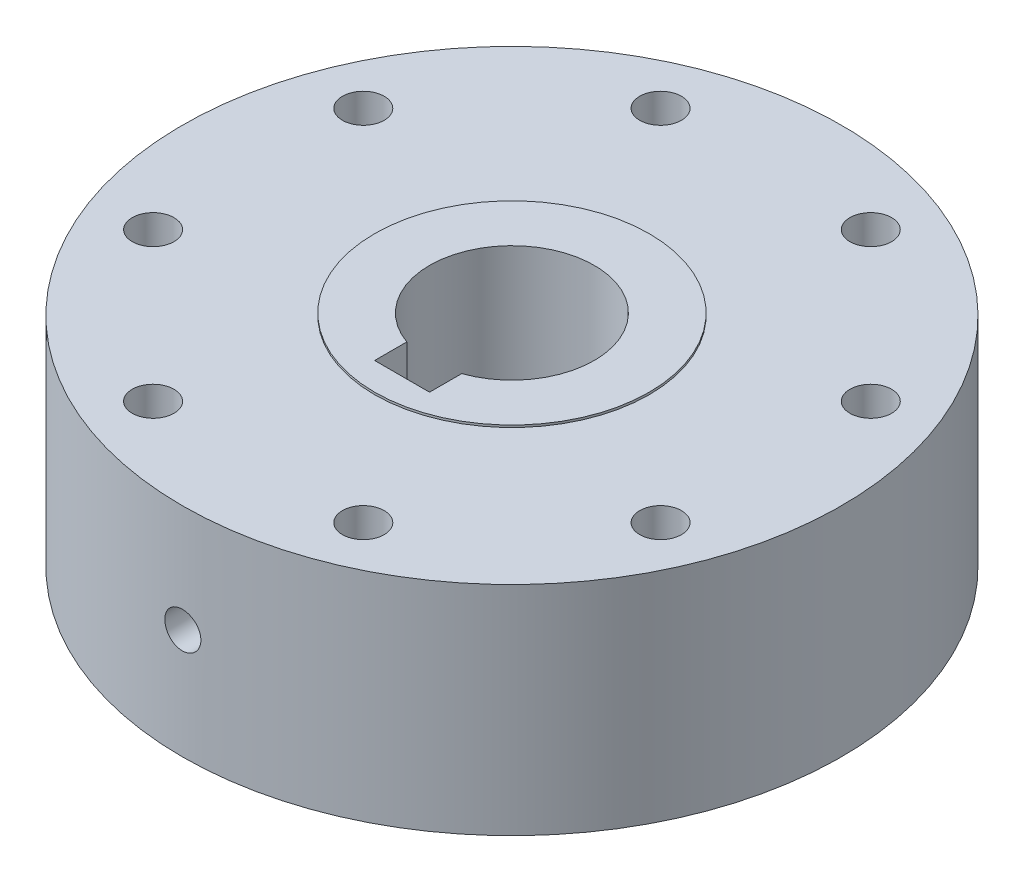
SolidWorks part; units mm, degrees
ref_plane "Front Plane" through (0, 0, 0) normal (0, 0, 1) x (1, 0, 0)
ref_plane "Top Plane" through (0, 0, 0) normal (0, 1, 0) x (1, 0, 0)
ref_plane "Right Plane" through (0, 0, 0) normal (1, 0, 0) x (0, 0, -1)
sketch "Sketch1" plane through (0, 0, 0) normal (0, 1, 0) x (1, 0, 0)
  circle A0 centre (0, 0) radius 38.1
  circle A1 centre (0, 0) radius 9.525
  dimension "D1" = 76.2
  dimension "D2" = 19.05
extrude "Boss-Extrude1" add sketch "Sketch1" along normal blind 25.4
hole_wizard "#10-32 Tapped Hole1" positions "Sketch3" profile "Sketch2" tap size "#10-32" standard "Ansi Inch" end condition through all
sketch "Sketch3" plane through (0, 25.4, 0) normal (0, 1, 0) x (-1, 0, 0)
  line L0 (38.1, 0) -> (0, 0) construction
  line L1 (0, 0) -> (29.3332, -12.1502) construction
  circle A0 centre (0, 0) radius 38.1 construction
  point P0 (29.3332, -12.1502)
  dimension "D1" = 31.75
  dimension "D2" = 22.5
sketch "Sketch2" plane through (-29.3332, 25.4, -12.1502) normal (1, 0, 0) x (0, 0, 1)
  line L0 (0, 0) -> (0, 25.4)
  line L1 (0, 25.4) -> (2.413, 25.4)
  line L2 (2.413, 25.4) -> (2.413, 0)
  line L5 (2.413, 0) -> (0, 0)
  line L11 (0, -6.35) -> (0, 107.95) construction
  dimension "Thread Major Dia." = 4.826
  dimension "Thru Tap Drill Depth" = 25.4
pattern_circular "CirPattern1" count 8 over 360 about axis through (0, 0, 0) along (0, 1, 0) of "#10-32 Tapped Hole1"
sketch "Sketch4" plane through (0, 25.4, 0) normal (0, 1, 0) x (1, 0, 0)
  line L1 (-3.175, -12.7) -> (3.175, -12.7)
  line L2 (-3.175, -12.7) -> (-3.175, -6.35)
  line L3 (-3.175, -6.35) -> (3.175, -6.35)
  line L4 (3.175, -12.7) -> (3.175, -6.35)
  line L5 (-3.175, -12.7) -> (3.175, -6.35) construction
  line L6 (-3.175, -6.35) -> (3.175, -12.7) construction
  circle A0 centre (0, 0) radius 9.525 construction
  point P0 (0, -9.525)
  dimension "D1" = 6.35
  dimension "D2" = 6.35
extrude "Cut-Extrude1" cut sketch "Sketch4" against normal through all
hole_wizard "#8-32 Tapped Hole1" positions "Sketch6" profile "Sketch5" tap size "#8-32" standard "Ansi Inch"
sketch "Sketch6" plane through (0, 0, 12.7) normal (0, 0, -1) x (-1, 0, 0)
  line L0 (3.175, 0) -> (-3.175, 0) construction
  line L1 (3.175, 0) -> (3.175, 25.4) construction
  point P0 (0, 12.7)
  dimension "D1" = 12.7
  dimension "D2" = 3.175
sketch "Sketch5" plane through (0, 12.7, 12.7) normal (1, 0, 0) x (0, 1, 0)
  line L0 (0, 0) -> (0, 25.4)
  line L1 (0, 25.4) -> (2.0828, 25.4)
  line L2 (2.0828, 25.4) -> (2.0828, 0)
  line L5 (2.0828, 0) -> (0, 0)
  line L11 (0, -6.35) -> (0, 107.95) construction
  dimension "Thread Major Dia." = 4.1656
  dimension "Thru Tap Drill Depth" = 25.4
sketch "Sketch7" plane through (0, 25.4, 0) normal (0, 1, 0) x (1, 0, 0)
  circle A0 centre (0, 0) radius 15.875
  dimension "D1" = 31.75
extrude "Cut-Extrude2" cut sketch "Sketch7" against normal blind 0.254 flip side to cut
